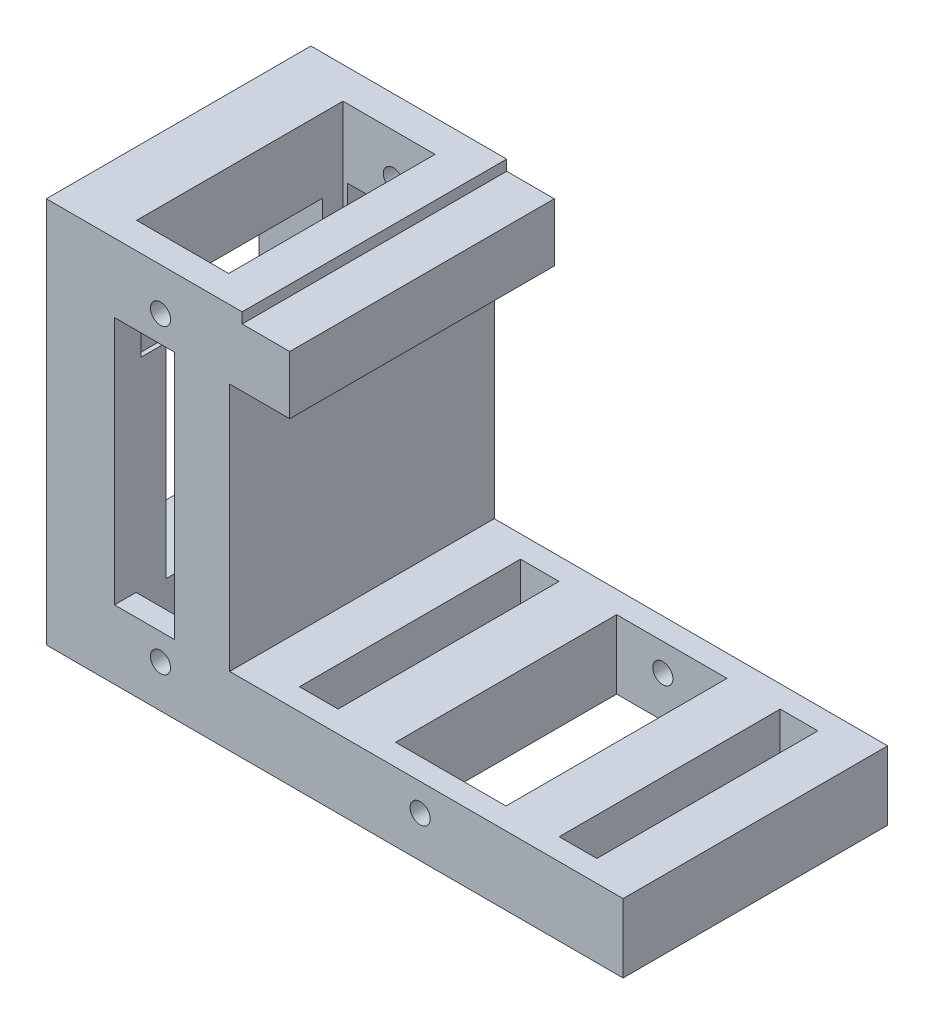
SolidWorks part; units mm, degrees
ref_plane "Front" through (0, 0, 0) normal (0, 0, 1) x (1, 0, 0)
ref_plane "Top" through (0, 0, 0) normal (0, 1, 0) x (1, 0, 0)
ref_plane "Right" through (0, 0, 0) normal (1, 0, 0) x (0, 0, -1)
sketch "Sketch1" plane through (0, 0, 0) normal (0, 1, 0) x (1, 0, 0)
  line L1 (0, 0) -> (109, 0)
  line L2 (0, 0) -> (0, 50)
  line L3 (0, 50) -> (109, 50)
  line L4 (109, 0) -> (109, 50)
  dimension "D1" = 50
  dimension "D2" = 109
extrude "Boss-Extrude1" add sketch "Sketch1" along normal blind 13
sketch "Sketch2" plane through (0, 0, 0) normal (0, -1, 0) x (-1, 0, 0)
  line L1 (-12.8746, 4.0842) -> (-33.047, 4.0842)
  line L2 (-12.8746, 4.0842) -> (-12.8746, 45.8523)
  line L3 (-12.8746, 45.8523) -> (-33.047, 45.8523)
  line L4 (-33.047, 4.0842) -> (-33.047, 45.8523)
  line L5 (-61.924, 4.0842) -> (-82.7872, 4.0842)
  line L6 (-61.924, 4.0842) -> (-61.924, 45.8523)
  line L7 (-61.924, 45.8523) -> (-82.7872, 45.8523)
  line L8 (-82.7872, 4.0842) -> (-82.7872, 45.8523)
  line L9 (-43.755, 4.0842) -> (-51.0502, 4.0842)
  line L10 (-43.755, 4.0842) -> (-43.755, 45.8523)
  line L11 (-43.755, 45.8523) -> (-51.0502, 45.8523)
  line L12 (-51.0502, 4.0842) -> (-51.0502, 45.8523)
  line L13 (-92.832, 4.0842) -> (-99.9614, 4.0842)
  line L14 (-92.832, 4.0842) -> (-92.832, 45.8523)
  line L15 (-92.832, 45.8523) -> (-99.9614, 45.8523)
  line L16 (-99.9614, 4.0842) -> (-99.9614, 45.8523)
extrude "Cut-Extrude1" cut sketch "Sketch2" against normal blind 16
sketch "Sketch4" plane through (0, 13, 0) normal (0, 1, 0) x (1, 0, 0)
  line L0 (109, 50) -> (0, 50) construction
  line L1 (0, 0) -> (12.8746, 0)
  line L2 (0, 0) -> (0, 50)
  line L3 (0, 50) -> (12.8746, 50)
  line L4 (12.8746, 0) -> (12.8746, 50)
  line L5 (141.3, 0) -> (0, 0) construction
  line L6 (34.6569, 0) -> (24.2664, 0)
  line L7 (34.6569, 0) -> (34.6569, 50)
  line L8 (34.6569, 50) -> (24.2664, 50)
  line L9 (24.2664, 0) -> (24.2664, 50)
  line L10 (242.5843, 50) -> (-181.9157, 50) construction
extrude "Boss-Extrude2" add sketch "Sketch4" along normal blind 47.03
sketch "Sketch5" plane through (0, 0, 0) normal (-1, 0, 0) x (0, 0, 1)
  line L1 (0, 73.03) -> (-50, 73.03)
  line L2 (0, 73.03) -> (0, 60.03)
  line L3 (0, 60.03) -> (-50, 60.03)
  line L4 (-50, 73.03) -> (-50, 60.03)
extrude "Boss-Extrude3" add sketch "Sketch5" against normal blind 46
sketch "Sketch6" plane through (0, 73.03, 0) normal (0, 1, 0) x (1, 0, 0)
  line L0 (46, 0) -> (0, 0) construction
  line L1 (46, 50) -> (37.0059, 50)
  line L2 (46, 50) -> (46, 0)
  line L3 (46, 0) -> (37.0059, 0)
  line L4 (37.0059, 50) -> (37.0059, 0)
extrude "Cut-Extrude2" cut sketch "Sketch6" against normal blind 2
sketch "Sketch7" plane through (0, 73.03, 0) normal (0, 1, 0) x (1, 0, 0)
  line L0 (37.0059, 0) -> (0, 0) construction
  line L1 (29.4647, 5) -> (12.0602, 5)
  line L2 (29.4647, 5) -> (29.4647, 44)
  line L3 (29.4647, 44) -> (12.0602, 44)
  line L4 (12.0602, 5) -> (12.0602, 44)
  dimension "D1" = 5
extrude "Cut-Extrude3" cut sketch "Sketch7" against normal blind 22
sketch "Sketch8" plane through (0, 0, 0) normal (-1, 0, 0) x (0, 0, 1)
  line L1 (-40.1645, 59.0842) -> (-9.7341, 59.0842)
  line L2 (-40.1645, 59.0842) -> (-40.1645, 12.4242)
  line L3 (-40.1645, 12.4242) -> (-9.7341, 12.4242)
  line L4 (-9.7341, 59.0842) -> (-9.7341, 12.4242)
extrude "Cut-Extrude4" cut sketch "Sketch8" against normal blind 22
sketch "Sketch9" plane through (0, 0, 0) normal (0, 0, 1) x (1, 0, 0)
  circle A0 centre (21.5799, 65.0119) radius 1.9
  circle A1 centre (21.5786, 8.0078) radius 1.9
  circle A2 centre (70.65, 7.798) radius 1.9
extrude "Cut-Extrude5" cut sketch "Sketch9" against normal blind 60
